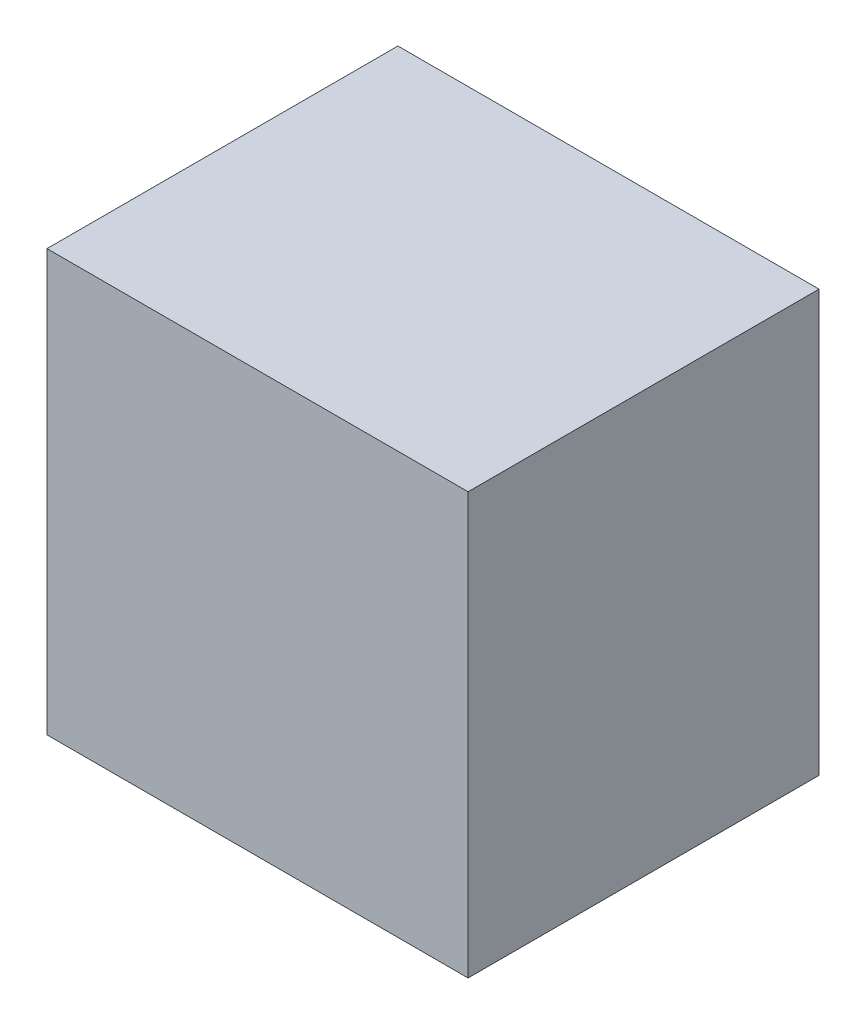
SolidWorks part; units mm, degrees
material "Dummy reaction wheel v5"
ref_plane "Front Plane" through (0, 0, 0) normal (0, 0, 1) x (1, 0, 0)
ref_plane "Top Plane" through (0, 0, 0) normal (0, 1, 0) x (1, 0, 0)
ref_plane "Right Plane" through (0, 0, 0) normal (1, 0, 0) x (0, 0, -1)
sketch "Body sketch" plane through (0, 0, 0) normal (0, 0, 1) x (1, 0, 0)
  line L1 (0, 0) -> (36, 0)
  line L2 (0, 0) -> (0, 36)
  line L3 (0, 36) -> (36, 36)
  line L4 (36, 0) -> (36, 36)
extrude "Body" add sketch "Body sketch" along normal blind 30
